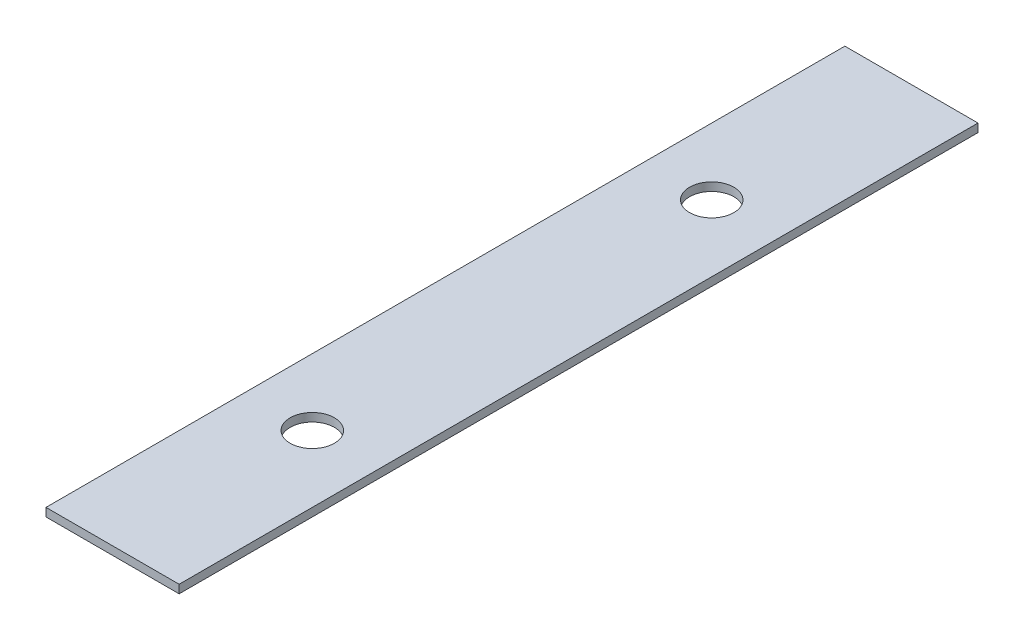
SolidWorks part; units mm, degrees
ref_plane "Front Plane" through (0, 0, 0) normal (0, 0, 1) x (1, 0, 0)
ref_plane "Top Plane" through (0, 0, 0) normal (0, 1, 0) x (1, 0, 0)
ref_plane "Right Plane" through (0, 0, 0) normal (1, 0, 0) x (0, 0, -1)
sketch "Sketch1" plane through (0, 0, 0) normal (0, 1, 0) x (1, 0, 0)
  line L1 (0, 0) -> (25.4, 0)
  line L2 (0, 0) -> (0, 152.4)
  line L3 (0, 152.4) -> (25.4, 152.4)
  line L4 (25.4, 0) -> (25.4, 152.4)
  dimension "D1" = 25.4
  dimension "D2" = 152.4
extrude "Boss-Extrude1" add sketch "Sketch1" along normal blind 1.5875
sketch "Sketch2" plane through (0, 1.5875, 0) normal (0, 1, 0) x (1, 0, 0)
  line L0 (25.4, 152.4) -> (0, 152.4) construction
  line L2 (0, 152.4) -> (0, 0) construction
  point P0 (12.7, 114.3)
  point P1 (12.7, 38.1)
  dimension "D1" = 76.2
  dimension "D2" = 38.1
  dimension "D3" = 12.7
  dimension "D4" = 12.7
hole_wizard "Tap Drill for 3/8-24 Tap1" positions "Sketch4" profile "Sketch3" hole size "3/8-24" standard "ANSI Inch" end condition through all
sketch "Sketch4" plane through (0, 1.5875, 0) normal (0, 1, 0) x (1, 0, 0)
  point P0 (12.7, 114.3)
  point P2 (12.7, 38.1)
sketch "Sketch3" plane through (12.7, 1.5875, -114.3) normal (1, 0, 0) x (0, 0, 1)
  line L0 (0, 0) -> (0, 1.5875)
  line L1 (0, 1.5875) -> (4.2164, 1.5875)
  line L2 (4.2164, 1.5875) -> (4.2164, 0)
  line L5 (4.2164, 0) -> (0, 0)
  line L11 (0, -6.35) -> (0, 107.95) construction
  dimension "Thru Hole Dia." = 8.4328
  dimension "Thru Hole Depth" = 1.5875
